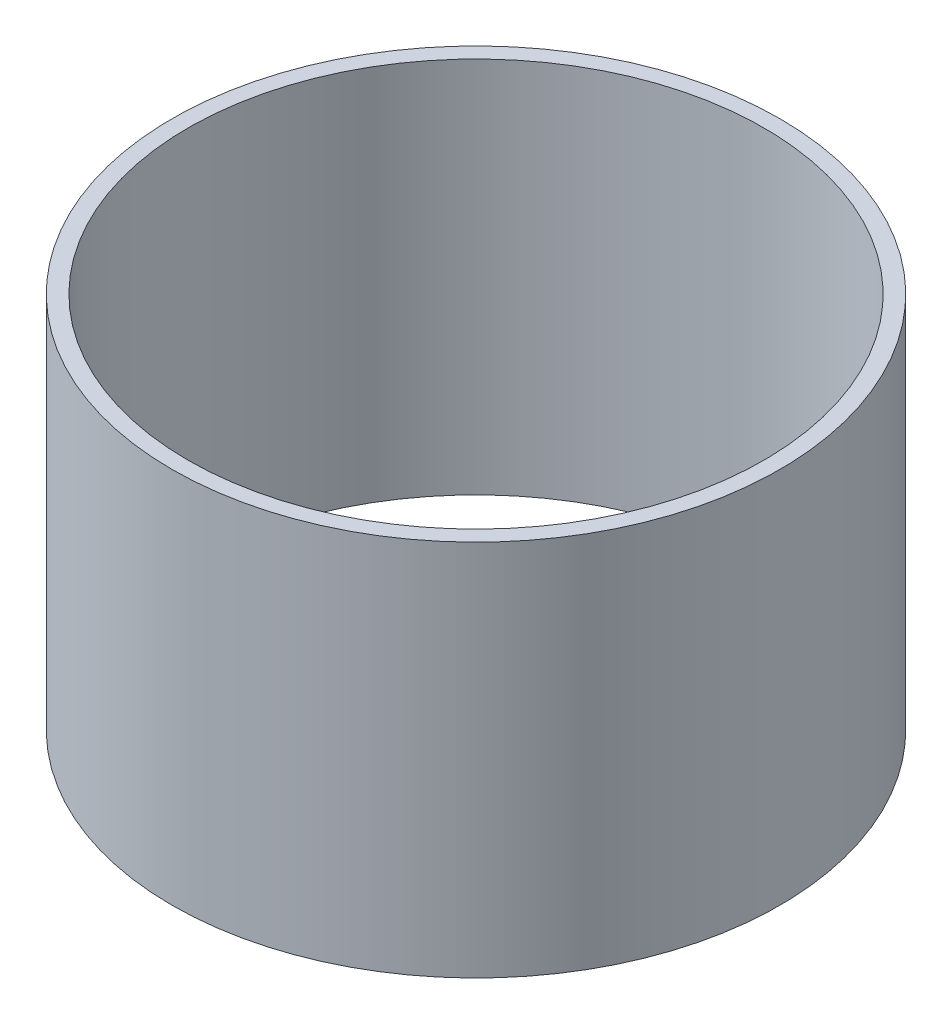
SolidWorks part; units mm, degrees
ref_plane "Front Plane" through (0, 0, 0) normal (0, 0, 1) x (1, 0, 0)
ref_plane "Top Plane" through (0, 0, 0) normal (0, 1, 0) x (1, 0, 0)
ref_plane "Right Plane" through (0, 0, 0) normal (1, 0, 0) x (0, 0, -1)
sketch "Sketch1" plane through (0, 0, 0) normal (0, 1, 0) x (1, 0, 0)
  circle A0 centre (0, 0) radius 24.15
  circle A1 centre (0, 0) radius 22.88
  dimension "D1" = 48.3
  dimension "D2" = 1.27
extrude "Boss-Extrude1" add sketch "Sketch1" along normal blind 30
